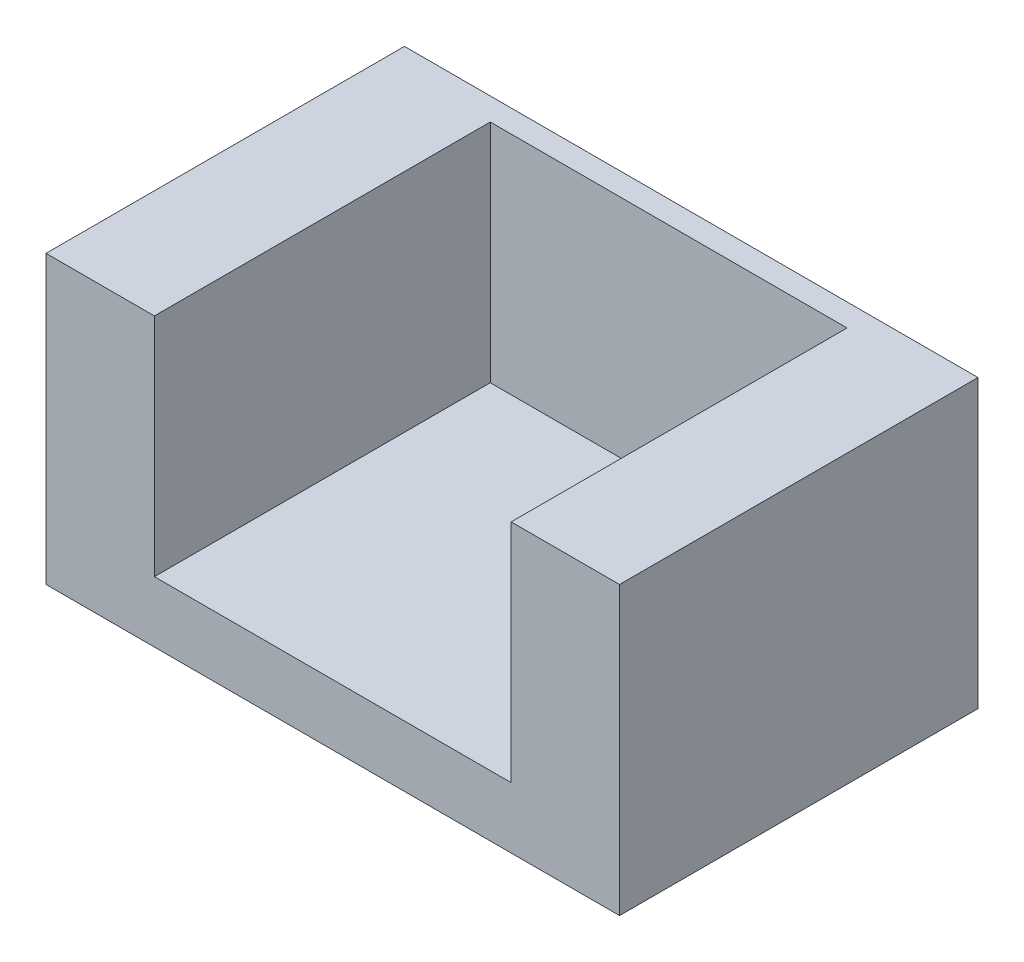
SolidWorks part; units mm, degrees
ref_plane "Front Plane" through (0, 0, 0) normal (0, 0, 1) x (1, 0, 0)
ref_plane "Top Plane" through (0, 0, 0) normal (0, 1, 0) x (1, 0, 0)
ref_plane "Right Plane" through (0, 0, 0) normal (1, 0, 0) x (0, 0, -1)
sketch "Sketch1" plane through (0, 0, 0) normal (0, 1, 0) x (1, 0, 0)
  line L1 (-19.0931, 5.9768) -> (6.3069, 5.9768)
  line L2 (-19.0931, 5.9768) -> (-19.0931, -9.8982)
  line L3 (-19.0931, -9.8982) -> (6.3069, -9.8982)
  line L4 (6.3069, 5.9768) -> (6.3069, -9.8982)
  dimension "D1" = 15.875
  dimension "D2" = 25.4
extrude "Boss-Extrude1" add sketch "Sketch1" along normal blind 12.7
sketch "Sketch2" plane through (0, 12.7, 0) normal (0, 1, 0) x (1, 0, 0)
  line L0 (-19.0931, 5.9768) -> (-19.0931, -9.8982) construction
  line L1 (-14.2931, 4.9768) -> (1.5069, 4.9768)
  line L2 (-14.2931, 4.9768) -> (-14.2931, -9.8982)
  line L3 (-14.2931, -9.8982) -> (1.5069, -9.8982)
  line L4 (1.5069, 4.9768) -> (1.5069, -9.8982)
  line L5 (6.3069, -9.8982) -> (6.3069, 5.9768) construction
  line L6 (6.3069, 5.9768) -> (-19.0931, 5.9768) construction
  line L7 (-19.0931, -9.8982) -> (6.3069, -9.8982) construction
  dimension "D1" = 4.8
  dimension "D2" = 4.8
  dimension "D3" = 1
  dimension "D4" = 0
extrude "Cut-Extrude1" cut sketch "Sketch2" against normal blind 10
